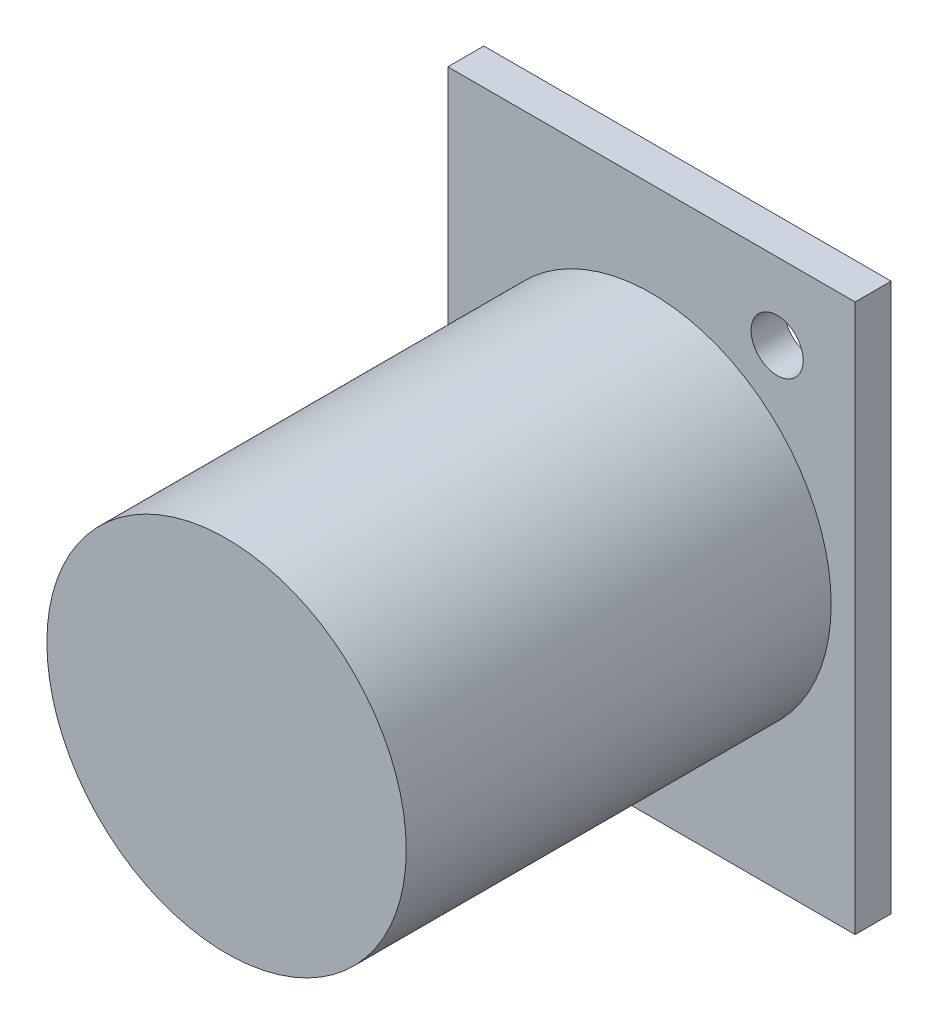
SolidWorks part; units mm, degrees
ref_plane "Front Plane" through (0, 0, 0) normal (0, 0, 1) x (1, 0, 0)
ref_plane "Top Plane" through (0, 0, 0) normal (0, 1, 0) x (1, 0, 0)
ref_plane "Right Plane" through (0, 0, 0) normal (1, 0, 0) x (0, 0, -1)
sketch "Sketch1" plane through (0, 0, 0) normal (0, 0, 1) x (1, 0, 0)
  line L1 (0, 0) -> (27.0002, 0)
  line L2 (0, 0) -> (0, 36.322)
  line L3 (0, 36.322) -> (27.0002, 36.322)
  line L4 (27.0002, 0) -> (27.0002, 36.322)
  dimension "D1" = 36.322
  dimension "D2" = 27.0002
extrude "Boss-Extrude1" add sketch "Sketch1" along normal blind 2.3876
sketch "Sketch2" plane through (0, 0, 2.3876) normal (0, 0, 1) x (1, 0, 0)
  line L0 (13.5001, 36.322) -> (13.5001, 0) construction
  line L1 (27.0002, 36.322) -> (0, 36.322) construction
  line L2 (0, 0) -> (27.0002, 0) construction
  line L3 (0, 18.161) -> (27.0002, 18.161) construction
  line L4 (0, 36.322) -> (0, 0) construction
  line L5 (27.0002, 0) -> (27.0002, 36.322) construction
  circle A0 centre (13.5001, 18.161) radius 11.9126
  dimension "D1" = 23.8252
extrude "Boss-Extrude2" add sketch "Sketch2" along normal blind 28.1686
sketch "Sketch3" plane through (0, 0, 0) normal (0, 0, -1) x (-1, 0, 0)
  line L0 (-27.0002, 18.161) -> (0, 18.161) construction
  line L1 (-27.0002, 0) -> (-27.0002, 36.322) construction
  line L2 (0, 36.322) -> (0, 0) construction
  line L3 (-13.5001, 36.322) -> (-13.5001, 0) construction
  line L4 (-27.0002, 36.322) -> (0, 36.322) construction
  line L5 (0, 0) -> (-27.0002, 0) construction
  circle A0 centre (-13.5001, 18.161) radius 10.6426
  dimension "D1" = 21.2852
extrude "Cut-Extrude1" cut sketch "Sketch3" against normal blind 28.1686
sketch "Sketch4" plane through (0, 0, 0) normal (0, 0, -1) x (-1, 0, 0)
  line L0 (-27.0002, 18.161) -> (0, 18.161) construction
  line L1 (-27.0002, 0) -> (-27.0002, 36.322) construction
  line L2 (0, 36.322) -> (0, 0) construction
  line L3 (-13.5001, 36.322) -> (-13.5001, 0) construction
  line L4 (-27.0002, 36.322) -> (0, 36.322) construction
  line L5 (0, 0) -> (-27.0002, 0) construction
  circle A0 centre (-21.8313, 31.242) radius 1.7272
  circle A1 centre (-5.1689, 5.08) radius 1.7272
  dimension "D1" = 3.4544
  dimension "D2" = 16.6624
  dimension "D3" = 26.162
  dimension "D4" = 13.081
  dimension "D5" = 8.3312
extrude "Cut-Extrude2" cut sketch "Sketch4" against normal up to next
chamfer "Chamfer1" distance 1.1303 angle 8 2 edges at (3.4417, 5.08, 0) (20.1041, 31.242, 0)
